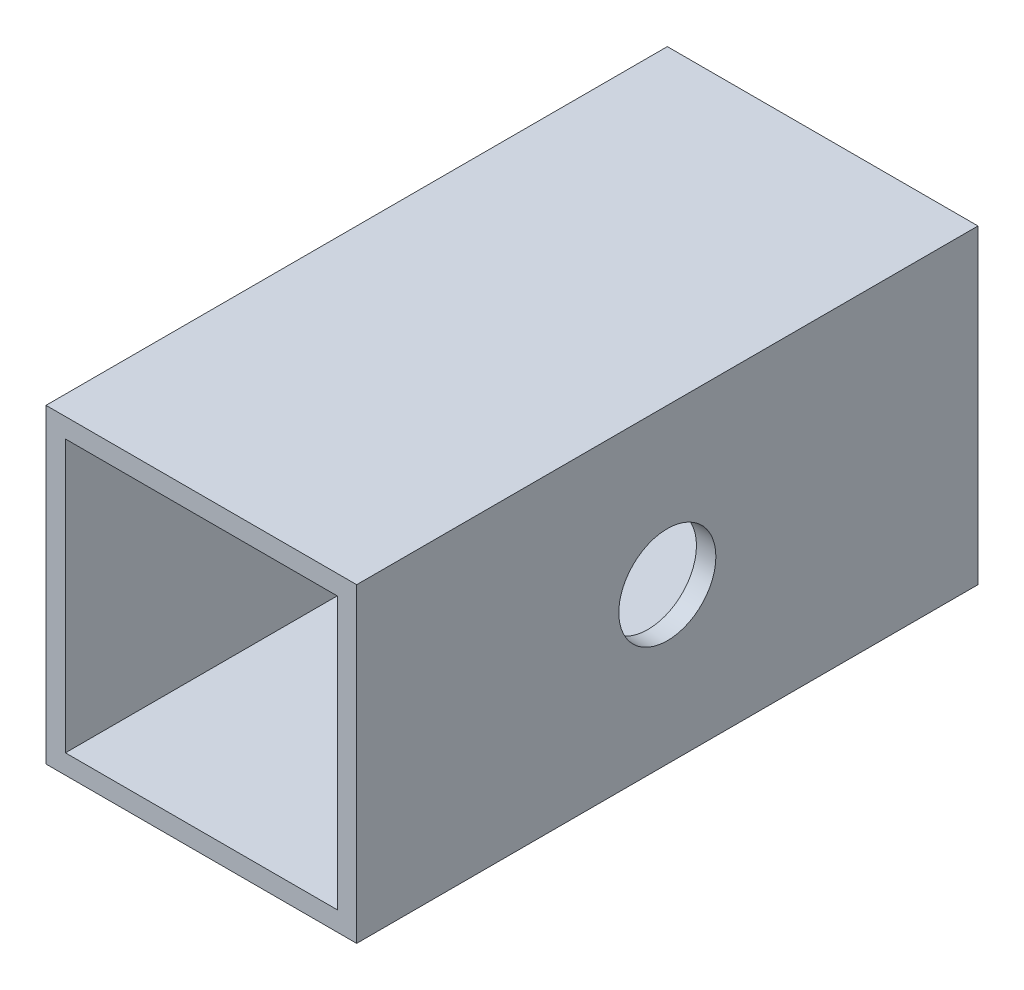
SolidWorks part; units mm, degrees
material "6063-T6"
ref_plane "Front Plane" through (0, 0, 0) normal (0, 0, 1) x (1, 0, 0)
ref_plane "Top Plane" through (0, 0, 0) normal (0, 1, 0) x (1, 0, 0)
ref_plane "Right Plane" through (0, 0, 0) normal (1, 0, 0) x (0, 0, -1)
sketch "Sketch1" plane through (0, 0, 0) normal (0, 0, 1) x (1, 0, 0)
  line L1 (-12.7, -12.7) -> (12.7, -12.7)
  line L2 (-12.7, -12.7) -> (-12.7, 12.7)
  line L3 (-12.7, 12.7) -> (12.7, 12.7)
  line L4 (12.7, -12.7) -> (12.7, 12.7)
  line L5 (-12.7, -12.7) -> (12.7, 12.7) construction
  line L6 (-12.7, 12.7) -> (12.7, -12.7) construction
  line L7 (-11.1125, -11.1125) -> (11.1125, -11.1125)
  line L8 (-11.1125, -11.1125) -> (-11.1125, 11.1125)
  line L9 (-11.1125, 11.1125) -> (11.1125, 11.1125)
  line L10 (11.1125, -11.1125) -> (11.1125, 11.1125)
  line L11 (-11.1125, -11.1125) -> (11.1125, 11.1125) construction
  line L12 (-11.1125, 11.1125) -> (11.1125, -11.1125) construction
  point P0 (0, 0)
  point P6 (0, 0)
  dimension "D1" = 25.4
  dimension "D2" = 22.225
extrude "Boss-Extrude1" add sketch "Sketch1" along normal blind 50.8
sketch "Sketch2" plane through (12.7, 0, 0) normal (1, 0, 0) x (0, 0, -1)
  line L0 (-50.8, 12.7) -> (0, -12.7) construction
  line L1 (0, 12.7) -> (-50.8, -12.7) construction
  circle A0 centre (-25.4, 0) radius 3.9688
  dimension "D1" = 7.9375
extrude "Cut-Extrude2" cut sketch "Sketch2" against normal through all
